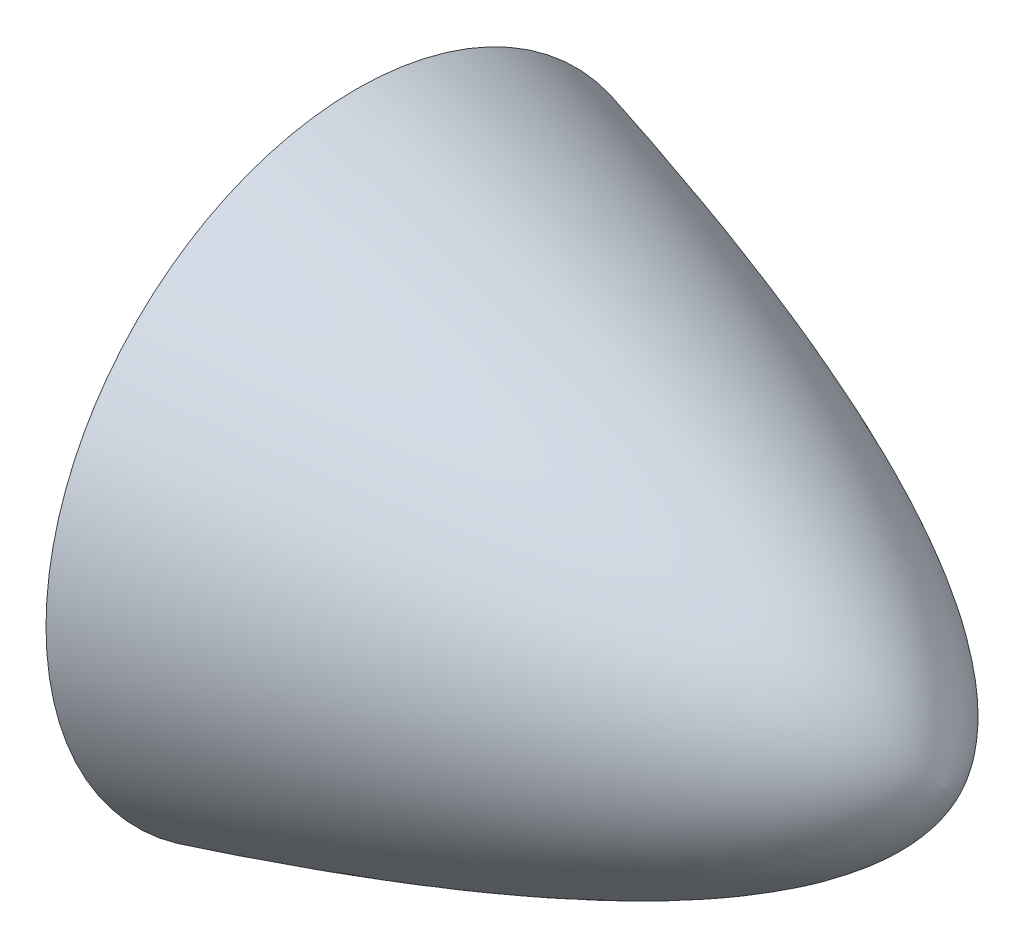
SolidWorks part; units mm, degrees
ref_plane "Front Plane" through (0, 0, 0) normal (0, 0, 1) x (1, 0, 0)
ref_plane "Top Plane" through (0, 0, 0) normal (0, 1, 0) x (1, 0, 0)
ref_plane "Right Plane" through (0, 0, 0) normal (1, 0, 0) x (0, 0, -1)
sketch "Sketch1" plane through (0, 0, 0) normal (0, 0, 1) x (1, 0, 0)
  line L0 (0, 0) -> (0, 19.05)
  line L1 (0, 0) -> (36.1685, 0)
  spline S0 degree 2 poles (0, 19.05) (34.5088, 9.8413) (36.1685, 0) knots 0 0 0 1 1 1
  point P3 (17.0549, 0)
  point P5 (0, 19.05)
  point P6 (36.1685, 0)
  dimension "D1" = 19.05
revolve "Revolve1" add sketch "Sketch1" angle 360 about L1
